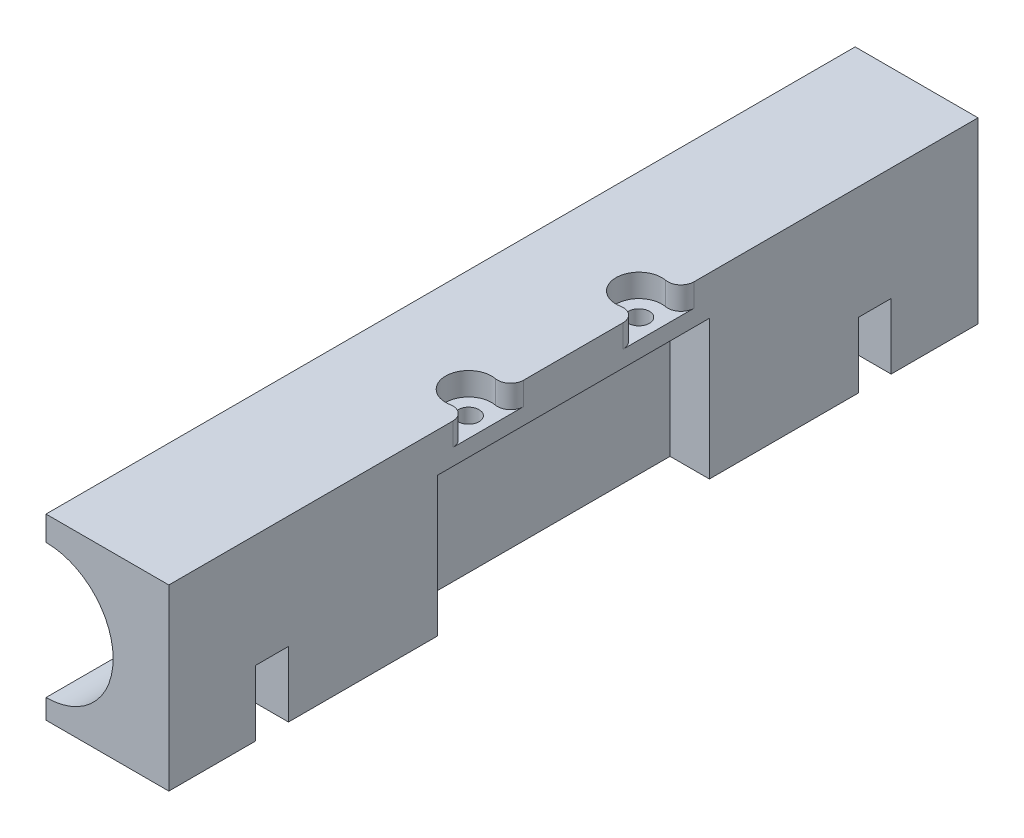
SolidWorks part; units mm, degrees
material "ABS"
ref_plane "前视基准面" through (0, 0, 0) normal (0, 0, 1) x (1, 0, 0)
ref_plane "上视基准面" through (0, 0, 0) normal (0, 1, 0) x (1, 0, 0)
ref_plane "右视基准面" through (0, 0, 0) normal (1, 0, 0) x (0, 0, -1)
other "Configuration Table"
sketch "草图1" plane through (0, 0, 0) normal (0, 1, 0) x (1, 0, 0)
  line L0 (0, -20.75) -> (0, 20.75) construction
  line L1 (-3, -20.75) -> (3, -20.75)
  line L2 (-3, -20.75) -> (-3, 20.75)
  line L3 (-3, 20.75) -> (3, 20.75)
  line L4 (3, -20.75) -> (3, 20.75)
  line L5 (-3, -20.75) -> (3, 20.75) construction
  line L6 (-3, 20.75) -> (3, -20.75) construction
  circle A0 centre (0, 13) radius 1.6
  circle A1 centre (0, -13) radius 1.6
  point P0 (0, 0)
  dimension "D3" = 3.2
  dimension "D4" = 3.2
  dimension "D5" = 26
  dimension "D1" = 6
  dimension "D2" = 41.5
  dimension "D6" = 13
extrude "凸台-拉伸1" add sketch "草图1" along normal blind 3
sketch "草图2" plane through (0, 0, 20.75) normal (0, 0, 1) x (1, 0, 0)
  line L0 (-5.5, 0) -> (-5.5, -16) construction
  line L1 (-5.5, -8) -> (-15.75, -8) construction
  line L2 (-5.5, -8) -> (-5.5, 0) construction
  line L3 (-15.75, 2.25) -> (-15.75, 3)
  line L4 (-15.75, 3) -> (-5.5, 3)
  line L5 (-5.5, 3) -> (-5.5, 0) construction
  line L6 (-3, 0) -> (3, 0) construction
  line L7 (-3, 3) -> (-3, 0) construction
  line L8 (-5.5, 3) -> (-3, 3)
  line L9 (-5.5, 3) -> (-5.5, -8)
  line L10 (-5.5, -8) -> (-3, -8)
  line L11 (-3, 3) -> (-3, -8)
  line L12 (-3, 3) -> (3, 3) construction
  arc A0 (-5.5, -8) -> (-15.75, 2.25) centre (-15.75, -8) ccw
  line M7 (-3, 3) -> (-3, 0)
  dimension "D3" = 2.5
  dimension "D1" = 16
  dimension "D2" = 10.25
extrude "凸台-拉伸2" add sketch "草图2" against normal up to surface (41.5 mm away) contours A0 L9 L4 L3 | L11 L8 L9 L10 M7 up to face at (0, 1.5, -20.75)
sketch "草图4" plane through (0, 0, 20.75) normal (0, 0, 1) x (1, 0, 0)
  line L0 (-3, -8) -> (3, -8)
  line L1 (3, -8) -> (3, 0)
  line L5 (-3, 0) -> (3, 0)
  line L6 (3, 0) -> (3, 3)
  line L7 (3, 3) -> (-15.75, 3)
  line L11 (3, 0) -> (3, 3)
  line L12 (3, 3) -> (-15.75, 3)
  line L16 (-15.75, 3) -> (-15.75, 2.25)
  line L17 (-15.75, 3) -> (-15.75, 2.25)
  line L20 (-5.5, -8) -> (-3, -8)
  line L21 (-5.5, -8) -> (-3, -8)
  line L22 (-3, -8) -> (-3, 0)
  line L23 (-3, -8) -> (-3, 0)
  circle A0 centre (-15.75, -8) radius 10.25
  arc A5 (-5.5, -8) -> (-15.75, 2.25) centre (-15.75, -8) ccw
  arc A6 (-5.5, -8) -> (-15.75, 2.25) centre (-15.75, -8) ccw
  dimension "D2" = 20.5
  dimension "D1" = 0
extrude "凸台-拉伸3" add sketch "草图4" along normal blind 17
sketch "草图5" plane through (0, 0, 37.75) normal (0, 0, 1) x (1, 0, 0)
  line L0 (-15.75, -18.25) -> (-15.75, -21.25)
  line L1 (-15.75, -21.25) -> (3, -21.25)
  line L2 (3, -21.25) -> (3, -8)
  line L4 (-5.5, -8) -> (3, -8)
  line L6 (3, 3) -> (-15.75, 3)
  line L7 (-5.5, -8) -> (3, -8)
  line L10 (3, 3) -> (-15.75, 3)
  line L16 (3, -8) -> (3, 3)
  line L18 (3, -8) -> (3, 3)
  line L19 (-15.75, 3) -> (-15.75, 2.25)
  line L20 (-15.75, 3) -> (-15.75, 2.25)
  circle A0 centre (-15.75, -8) radius 10.25
  arc A2 (-5.5, -8) -> (-15.75, 2.25) centre (-15.75, -8) ccw
  arc A6 (-5.5, -8) -> (-15.75, 2.25) centre (-15.75, -8) ccw
  dimension "D1" = 20.5
  dimension "D3" = 3
  dimension "D2" = 0
extrude "凸台-拉伸4" add sketch "草图5" along normal blind 10
mirror "镜向1" about plane through (0, 0, 0) normal (0, 0, 1) of "凸台-拉伸4", "凸台-拉伸3"
sketch "草图6" plane through (0, 3, 0) normal (0, 1, 0) x (1, 0, 0)
  line L1 (-15.75, 47.75) -> (3, 47.75)
  line L2 (-15.75, 47.75) -> (-15.75, -47.75)
  line L3 (-15.75, -47.75) -> (3, -47.75)
  line L4 (3, 47.75) -> (3, -47.75)
  circle A0 centre (0, -13) radius 1.6 construction
  circle A1 centre (0, 13) radius 1.6 construction
  circle A2 centre (0, -13) radius 1.6
  circle A3 centre (0, 13) radius 1.6
extrude "凸台-拉伸5" add sketch "草图6" along normal blind 3
sketch "草图7" plane through (0, 0, -37.75) normal (0, 0, 1) x (1, 0, 0)
  line L4 (3, -8) -> (-5.5, -8)
  line L5 (-15.75, -18.25) -> (-15.75, -21.25)
  line L6 (-15.75, -21.25) -> (3, -21.25)
  line L7 (3, -21.25) -> (3, -8)
  line L8 (3, -8) -> (-5.5, -8)
  line L9 (-15.75, -18.25) -> (-15.75, -21.25)
  line L10 (-15.75, -21.25) -> (3, -21.25)
  line L11 (3, -21.25) -> (3, -8)
  arc A1 (-15.75, -18.25) -> (-5.5, -8) centre (-15.75, -8) ccw
  arc A4 (-15.75, -18.25) -> (-5.5, -8) centre (-15.75, -8) ccw
  dimension "D1" = 0
extrude "凸台-拉伸6" add sketch "草图7" along normal up to surface (75.5 mm away) up to face at (-5.7754, -15.7746, 37.75)
sketch "草图8" plane through (0, -8, 0) normal (0, 1, 0) x (1, 0, 0)
  line L4 (-3, 20.75) -> (-3, -20.75)
  line L5 (-3, -20.75) -> (3, -20.75)
  line L6 (3, -20.75) -> (3, 20.75)
  line L7 (3, 20.75) -> (-3, 20.75)
  line L8 (-3, 20.75) -> (-3, -20.75)
  line L9 (-3, -20.75) -> (3, -20.75)
  line L10 (3, -20.75) -> (3, 20.75)
  line L11 (3, 20.75) -> (-3, 20.75)
  dimension "D1" = 0
extrude "切除-拉伸1" cut sketch "草图8" against normal through all
sketch "草图9" plane through (0, 6, 0) normal (0, 1, 0) x (1, 0, 0)
  circle A0 centre (0, 13) radius 3.5
  circle A1 centre (0, -13) radius 3.5
  dimension "D1" = 7
  dimension "D2" = 7
extrude "切除-拉伸2" cut sketch "草图9" against normal blind 3.5
fillet "圆角1" radius 2 4 edges at (3, 4.25, -11.1972) (3, 4.25, -14.8028) (3, 4.25, 11.1972) (3, 4.25, 14.8028)
sketch "草图10" plane through (0, 0, 47.75) normal (0, 0, 1) x (1, 0, 0)
  line L5 (-15.75, -18.25) -> (-15.75, -21.25)
  line L6 (-15.75, -21.25) -> (3, -21.25)
  line L7 (3, -21.25) -> (3, 6)
  line L8 (3, 6) -> (-15.75, 6)
  line L9 (-15.75, 6) -> (-15.75, 2.25)
  line L10 (-15.75, -18.25) -> (-15.75, -21.25)
  line L11 (-15.75, -21.25) -> (3, -21.25)
  line L12 (3, -21.25) -> (3, 6)
  line L13 (3, 6) -> (-15.75, 6)
  line L14 (-15.75, 6) -> (-15.75, 2.25)
  arc A1 (-15.75, -18.25) -> (-15.75, 2.25) centre (-15.75, -8) ccw
  arc A2 (-15.75, -18.25) -> (-15.75, 2.25) centre (-15.75, -8) ccw
  dimension "D1" = 0
extrude "凸台-拉伸7" add sketch "草图10" along normal blind 14
sketch "草图11" plane through (0, 0, -47.75) normal (0, 0, -1) x (-1, 0, 0)
  line L5 (15.75, 2.25) -> (15.75, 6)
  line L6 (15.75, 6) -> (-3, 6)
  line L7 (-3, 6) -> (-3, -21.25)
  line L8 (-3, -21.25) -> (15.75, -21.25)
  line L9 (15.75, -21.25) -> (15.75, -18.25)
  line L10 (15.75, 2.25) -> (15.75, 6)
  line L11 (15.75, 6) -> (-3, 6)
  line L12 (-3, 6) -> (-3, -21.25)
  line L13 (-3, -21.25) -> (15.75, -21.25)
  line L14 (15.75, -21.25) -> (15.75, -18.25)
  arc A1 (15.75, 2.25) -> (15.75, -18.25) centre (15.75, -8) ccw
  arc A2 (15.75, 2.25) -> (15.75, -18.25) centre (15.75, -8) ccw
  dimension "D1" = 0
extrude "凸台-拉伸8" add sketch "草图11" along normal blind 14
sketch "草图12" plane through (3, 0, 0) normal (1, 0, 0) x (0, 0, -1)
  line L0 (45.99, -21.25) -> (45.99, -6.9123) construction
  line L1 (20.75, -21.25) -> (61.75, -21.25) construction
  line L2 (61.75, 6) -> (61.75, -21.25) construction
  line L3 (0, 0) -> (0, -21.25) construction
  line L4 (43.49, -21.25) -> (48.49, -21.25)
  line L5 (43.49, -21.25) -> (43.49, -11.25)
  line L6 (43.49, -11.25) -> (48.49, -11.25)
  line L7 (48.49, -21.25) -> (48.49, -11.25)
  line L8 (20.75, -21.25) -> (-20.75, -21.25) construction
  line L9 (-48.49, -21.25) -> (-48.49, -11.25)
  line L10 (-43.49, -11.25) -> (-48.49, -11.25)
  line L11 (-43.49, -21.25) -> (-43.49, -11.25)
  line L12 (-43.49, -21.25) -> (-48.49, -21.25)
  dimension "D1" = 15.76
  dimension "D2" = 5
  dimension "D3" = 10
extrude "切除-拉伸3" cut sketch "草图12" against normal through all
